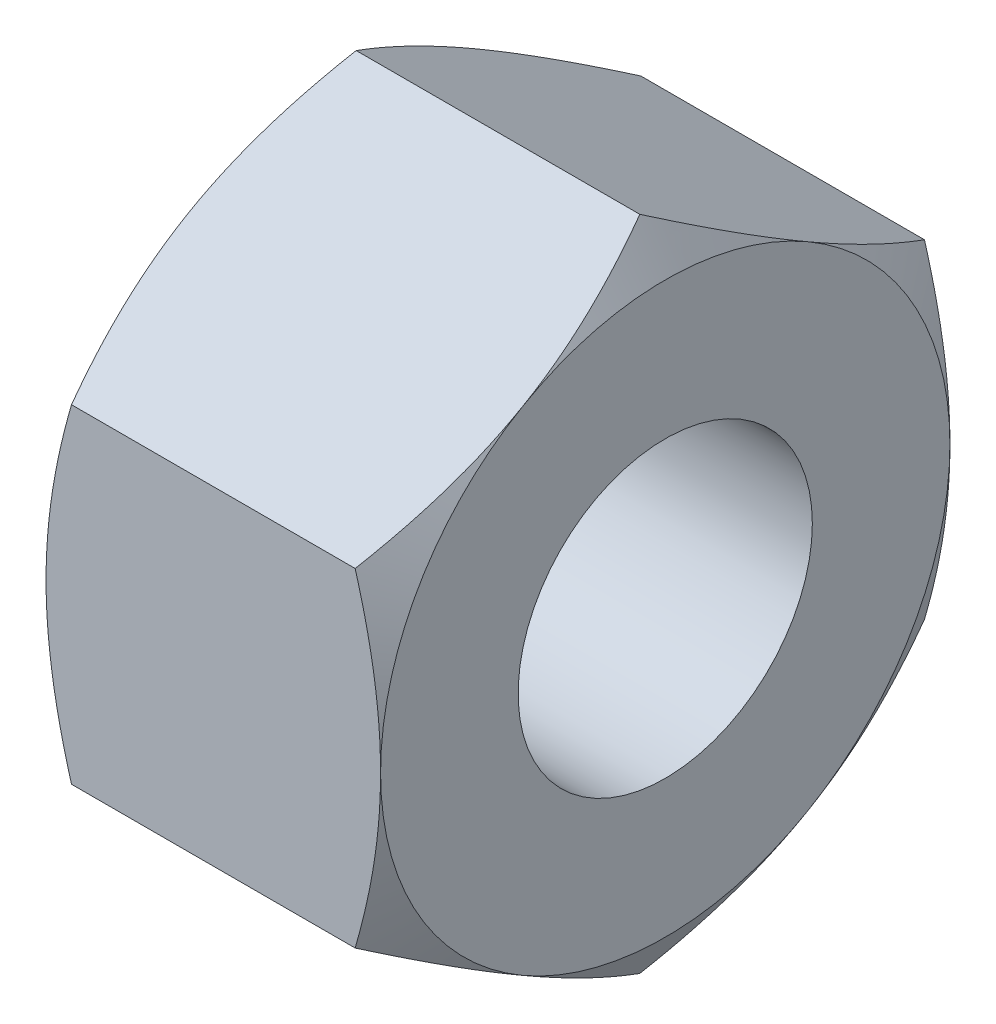
SolidWorks part; units mm, degrees
ref_plane "Front Plane" through (0, 0, 0) normal (0, 0, 1) x (1, 0, 0)
ref_plane "Top Plane" through (0, 0, 0) normal (0, 1, 0) x (1, 0, 0)
ref_plane "Right Plane" through (0, 0, 0) normal (1, 0, 0) x (0, 0, -1)
sketch "Sketch1" plane through (0, 0, 0) normal (1, 0, 0) x (0, 0, -1)
  line L1 (0, 4.6188) -> (-4, 2.3094)
  line L2 (-4, 2.3094) -> (-4, -2.3094)
  line L3 (-4, -2.3094) -> (0, -4.6188)
  line L4 (0, -4.6188) -> (4, -2.3094)
  line L5 (4, -2.3094) -> (4, 2.3094)
  line L6 (4, 2.3094) -> (0, 4.6188)
  circle A0 centre (0, 0) radius 4 construction
  dimension "MSM_59" = 8
extrude "Boss-Extrude1" add sketch "Sketch1" against normal blind 4.7
sketch "Sketch2" plane through (0, 0, 0) normal (1, 0, 0) x (0, 0, -1)
  circle A0 centre (0, 0) radius 4
  dimension "MSM_59" = 8
extrude "Cut-Extrude1" cut sketch "Sketch2" against normal through all draft 60 flip side to cut
sketch "Sketch3" plane through (-4.7, 0, 0) normal (-1, 0, 0) x (0, 0, 1)
  circle A0 centre (0, 0) radius 4
  dimension "MSM_59" = 8
extrude "Cut-Extrude2" cut sketch "Sketch3" against normal through all draft 60 flip side to cut
hole_wizard "Tap1" positions "Sketch5" profile "Sketch4" hole size "M1x0.25" standard "JIS" end condition through all
sketch "Sketch5" plane through (0, 0, 0) normal (1, 0, 0) x (0, 0, -1)
  point P0 (0, 0)
sketch "Sketch4" plane through (0, 0, 0) normal (0, 1, 0) x (0, 0, -1)
  line L0 (0, 0) -> (0, 4.7)
  line L1 (0, 4.7) -> (2.067, 4.7)
  line L2 (2.067, 4.7) -> (2.067, 0)
  line L5 (2.067, 0) -> (0, 0)
  line L11 (0, -6.35) -> (0, 107.95) construction
  dimension "STD_2" = 4.134
  dimension "Thru Hole Depth" = 4.7
cosmetic thread "Thread2" parameters "HTD_1"=5
